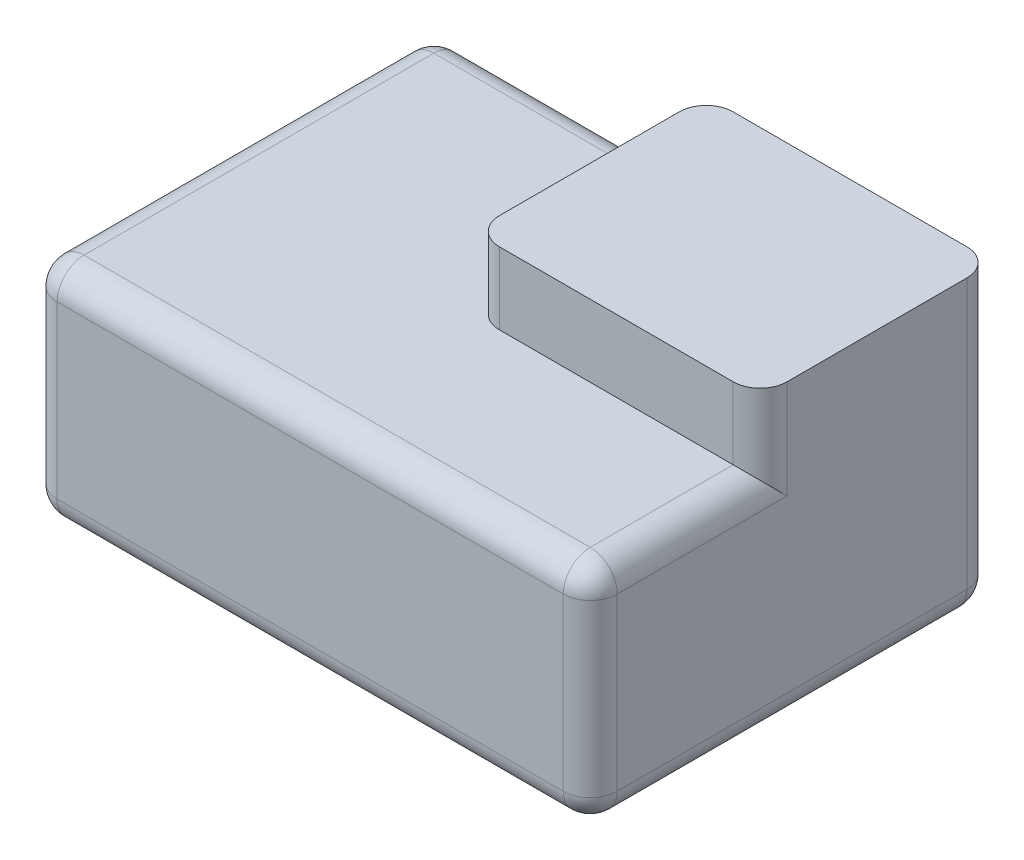
SolidWorks part; units mm, degrees
ref_plane "Спереди" through (0, 0, 0) normal (0, 0, 1) x (1, 0, 0)
ref_plane "Сверху" through (0, 0, 0) normal (0, 1, 0) x (1, 0, 0)
ref_plane "Справа" through (0, 0, 0) normal (1, 0, 0) x (0, 0, -1)
sketch "Эскиз1" plane through (0, 0, 0) normal (0, 1, 0) x (1, 0, 0)
  line L1 (0, 0) -> (62.3, 0)
  line L2 (0, 0) -> (0, 44.9)
  line L3 (0, 44.9) -> (62.3, 44.9)
  line L4 (62.3, 0) -> (62.3, 44.9)
  dimension "D1" = 44.9
  dimension "D2" = 62.3
extrude "Бобышка-Вытянуть1" add sketch "Эскиз1" along normal blind 33
sketch "Эскиз3" plane through (0, 33, 0) normal (0, 1, 0) x (1, 0, 0)
  line L1 (62.3, 44.9) -> (30.3, 44.9)
  line L2 (62.3, 44.9) -> (62.3, 18.9)
  line L3 (62.3, 18.9) -> (30.3, 18.9)
  line L4 (30.3, 44.9) -> (30.3, 18.9)
  line L5 (62.3, 44.9) -> (0, 44.9)
  line L6 (62.3, 44.9) -> (62.3, 0)
  line L7 (62.3, 0) -> (0, 0)
  line L8 (0, 44.9) -> (0, 0)
  line M1 (0, 44.9) -> (0, 0)
  line M2 (0, 0) -> (62.3, 0)
  line M3 (62.3, 0) -> (62.3, 44.9)
  line M4 (62.3, 44.9) -> (0, 44.9)
  dimension "D1" = 32
  dimension "D2" = 26
extrude "Вырез-Вытянуть1" cut sketch "Эскиз3" against normal blind 8 contours L4 L3 M4 M1 M2 M3
fillet "Скругление1" radius 3 15 edges at (0, 0, -22.45) (0, 12.5, -44.9) (31.15, 0, -44.9) (62.3, 16.5, -44.9) (62.3, 0, -22.45) (0, 12.5, 0) (62.3, 12.5, 0) (31.15, 0, 0) (0, 25, -22.45) (15.15, 25, -44.9) (30.3, 29, -44.9) (62.3, 25, -9.45) (62.3, 29, -18.9) (31.15, 25, 0) (30.3, 29, -18.9)
